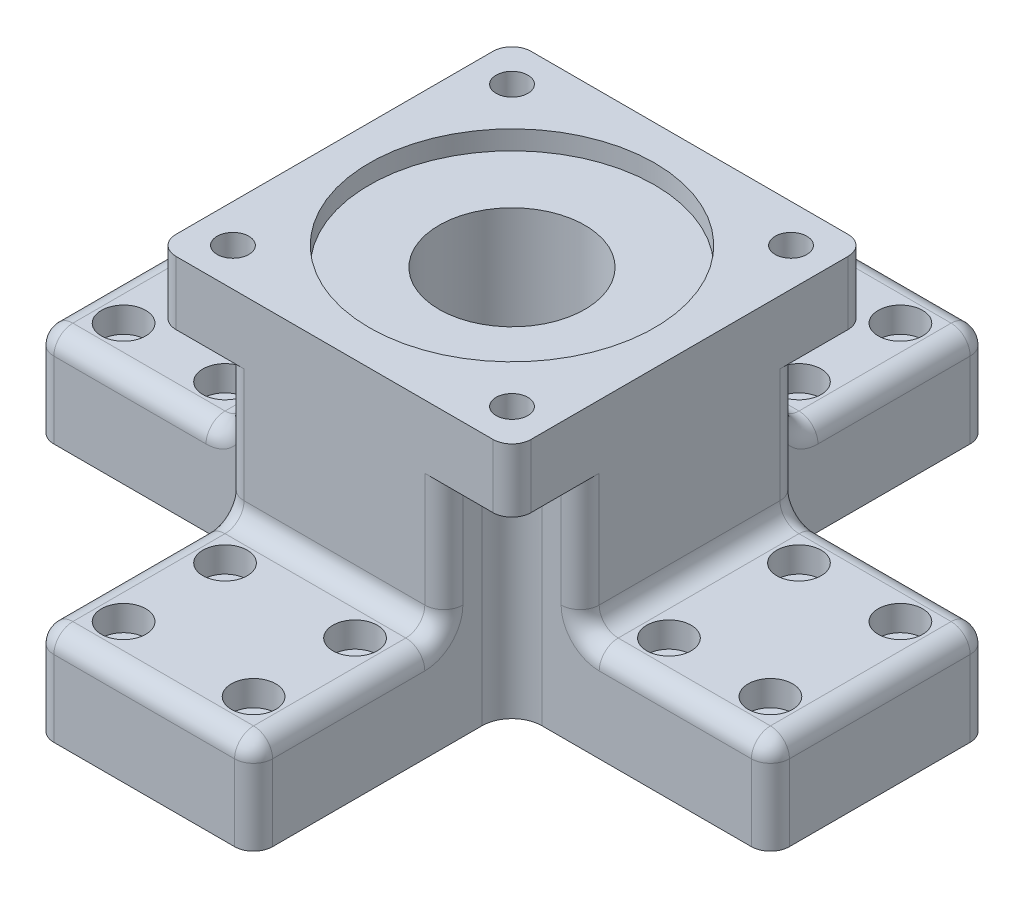
SolidWorks part; units mm, degrees
ref_plane "Front Plane" through (0, 0, 0) normal (0, 0, 1) x (1, 0, 0)
ref_plane "Top Plane" through (0, 0, 0) normal (0, 1, 0) x (1, 0, 0)
ref_plane "Right Plane" through (0, 0, 0) normal (1, 0, 0) x (0, 0, -1)
sketch "Sketch1" plane through (0, 0, 0) normal (0, 1, 0) x (1, 0, 0)
  line L1 (-28, -28) -> (28, -28)
  line L2 (-28, -28) -> (-28, 28)
  line L3 (-28, 28) -> (28, 28)
  line L4 (28, -28) -> (28, 28)
  line L5 (-28, -28) -> (28, 28) construction
  line L6 (-28, 28) -> (28, -28) construction
  point P0 (0, 0)
  dimension "D1" = 56
  dimension "D2" = 56
extrude "Boss-Extrude1" add sketch "Sketch1" along normal blind 46
sketch "Sketch2" plane through (0, 46, 0) normal (0, 1, 0) x (1, 0, 0)
  circle A0 centre (0, 0) radius 22.5
  dimension "D1" = 45
extrude "Cut-Extrude1" cut sketch "Sketch2" against normal blind 3
sketch "Sketch3" plane through (0, 43, 0) normal (0, 1, 0) x (1, 0, 0)
  circle A0 centre (0, 0) radius 11.5
  dimension "D1" = 23
extrude "Cut-Extrude2" cut sketch "Sketch3" against normal blind 50
sketch "Sketch4" plane through (0, 46, 0) normal (0, 1, 0) x (1, 0, 0)
  line L0 (0, 0) -> (0, 22) construction
  line L1 (0, 22) -> (-22, 22) construction
  line L2 (0, 0) -> (41.4914, 0) construction
  circle A1 centre (-22, 22) radius 2.5
  circle A2 centre (22, 22) radius 2.5
  circle A3 centre (22, -22) radius 2.5
  circle A4 centre (-22, -22) radius 2.5
  dimension "D3" = 5
  dimension "D1" = 22
  dimension "D2" = 22
extrude "Cut-Extrude3" cut sketch "Sketch4" against normal blind 10
sketch "Sketch5" plane through (0, 0, 0) normal (0, -1, 0) x (1, 0, 0)
  line L0 (0, 0) -> (0, 22) construction
  line L1 (0, 22) -> (-22, 22) construction
  line L2 (-22, 17.25) -> (-28, 17.25)
  line L3 (-28, -28) -> (-28, 28) construction
  line L4 (-28, 17.25) -> (-28, 28)
  line L5 (-17.25, 22) -> (-17.25, 28)
  line L6 (-28, 28) -> (28, 28) construction
  line L7 (-17.25, 28) -> (-28, 28)
  line L8 (17.25, 22) -> (17.25, 28)
  line L9 (17.25, 28) -> (28, 28)
  line L10 (28, 17.25) -> (28, 28)
  line L11 (22, 17.25) -> (28, 17.25)
  line L12 (0, 0) -> (52.0501, 0) construction
  line L13 (-28, -17.25) -> (-28, -28)
  line L14 (-17.25, -28) -> (-28, -28)
  line L15 (-17.25, -22) -> (-17.25, -28)
  line L16 (-22, -17.25) -> (-28, -17.25)
  line L17 (22, -17.25) -> (28, -17.25)
  line L18 (28, -17.25) -> (28, -28)
  line L19 (17.25, -28) -> (28, -28)
  line L20 (17.25, -22) -> (17.25, -28)
  circle A0 centre (-22, 22) radius 4.75 construction
  arc A1 (-22, 17.25) -> (-17.25, 22) centre (-22, 22) ccw
  arc A2 (22, 17.25) -> (17.25, 22) centre (22, 22) cw
  arc A3 (-22, -17.25) -> (-17.25, -22) centre (-22, -22) cw
  arc A4 (22, -17.25) -> (17.25, -22) centre (22, -22) ccw
  dimension "D3" = 9.5
  dimension "D1" = 22
  dimension "D2" = 22
extrude "Cut-Extrude4" cut sketch "Sketch5" against normal blind 36
sketch "Sketch6" plane through (0, 0, -28) normal (0, 0, -1) x (-1, 0, 0)
  line L0 (17.25, 36) -> (17.25, 0) construction
  line L1 (-17.25, 0) -> (17.25, 0)
  line L2 (-17.25, 0) -> (-17.25, 15)
  line L3 (-17.25, 15) -> (17.25, 15)
  line L4 (17.25, 0) -> (17.25, 15)
  dimension "D1" = 15
extrude "Boss-Extrude2" add sketch "Sketch6" along normal blind 30
sketch "Sketch7" plane through (0, 15, 0) normal (0, 1, 0) x (1, 0, 0)
  line L0 (-17.25, 28) -> (17.25, 58) construction
  line L1 (-10.25, 58) -> (-10.25, 51) construction
  line L2 (-17.25, 58) -> (17.25, 58) construction
  line L3 (-10.25, 51) -> (-17.25, 51) construction
  line L4 (-17.25, 58) -> (-17.25, 28) construction
  line L5 (0, 43) -> (0, 58) construction
  line L6 (0, 43) -> (-17.25, 43) construction
  circle A0 centre (-10.25, 51) radius 2.15
  circle A2 centre (10.25, 51) radius 2.15
  circle A3 centre (10.25, 35) radius 2.15
  circle A4 centre (-10.25, 35) radius 2.15
  dimension "D1" = 4.3
  dimension "D2" = 7
  dimension "D3" = 7
extrude "Cut-Extrude5" cut sketch "Sketch7" against normal blind 30
fillet "Fillet1" radius 3 1 edges at (0, 15, -28)
sketch "Sketch8" plane through (0, 15, 0) normal (0, 1, 0) x (1, 0, 0)
  circle A0 centre (-10.25, 51) radius 3.5
  circle A1 centre (10.25, 51) radius 3.5
  circle A2 centre (-10.25, 35) radius 3.5
  circle A3 centre (10.25, 35) radius 3.5
  dimension "D1" = 7
extrude "Cut-Extrude6" cut sketch "Sketch8" against normal blind 4
pattern_circular "CirPattern2" count 4 every 90 about axis through (0, 0, 0) along (0, 1, 0) of "Cut-Extrude6", "Cut-Extrude5", "Boss-Extrude2"
fillet "Fillet2" radius 3 3 edges at (28, 15, 0) (0, 15, 28) (-28, 15, 0)
fillet "Fillet3" radius 3 8 edges at (17.25, 7.5, -58) (-17.25, 7.5, -58) (-58, 7.5, -17.25) (-58, 7.5, 17.25) (-17.25, 7.5, 58) (17.25, 7.5, 58) (58, 7.5, 17.25) (58, 7.5, -17.25)
fillet "Fillet4" radius 3 31 edges at (17.25, 15.8787, -28.8787) (-17.25, 15.8787, -28.8787) (28.8787, 15.8787, 17.25) (28.8787, 15.8787, -17.25) (-28.8787, 15.8787, -17.25) (-28.8787, 15.8787, 17.25) (0, 15, -58) (17.25, 15, -43) (-17.25, 15, -43) (-16.3713, 15, -57.1213) (16.3713, 15, -57.1213) (58, 15, 0) (43, 15, -17.25) (43, 15, 17.25) (57.1213, 15, 16.3713) (57.1213, 15, -16.3713) (-58, 15, 0) (-43, 15, 17.25) (-43, 15, -17.25) (-57.1213, 15, -16.3713) (-57.1213, 15, 16.3713) (28, 27, 17.25) (-28, 27, -17.25) (-17.25, 27, -28) (28, 27, -17.25) (17.25, 27, -28) (28, 41, 28) (-28, 41, 28) (-28, 41, -28) (28, 41, -28) (-28, 27, 17.25)
fillet "Fillet5" radius 3 9 edges at (-17.25, 15.8787, 28.8787) (17.25, 15.8787, 28.8787) (0, 15, 58) (17.25, 15, 43) (-17.25, 15, 43) (-16.3713, 15, 57.1213) (16.3713, 15, 57.1213) (17.25, 27, 28) (-17.25, 27, 28)
